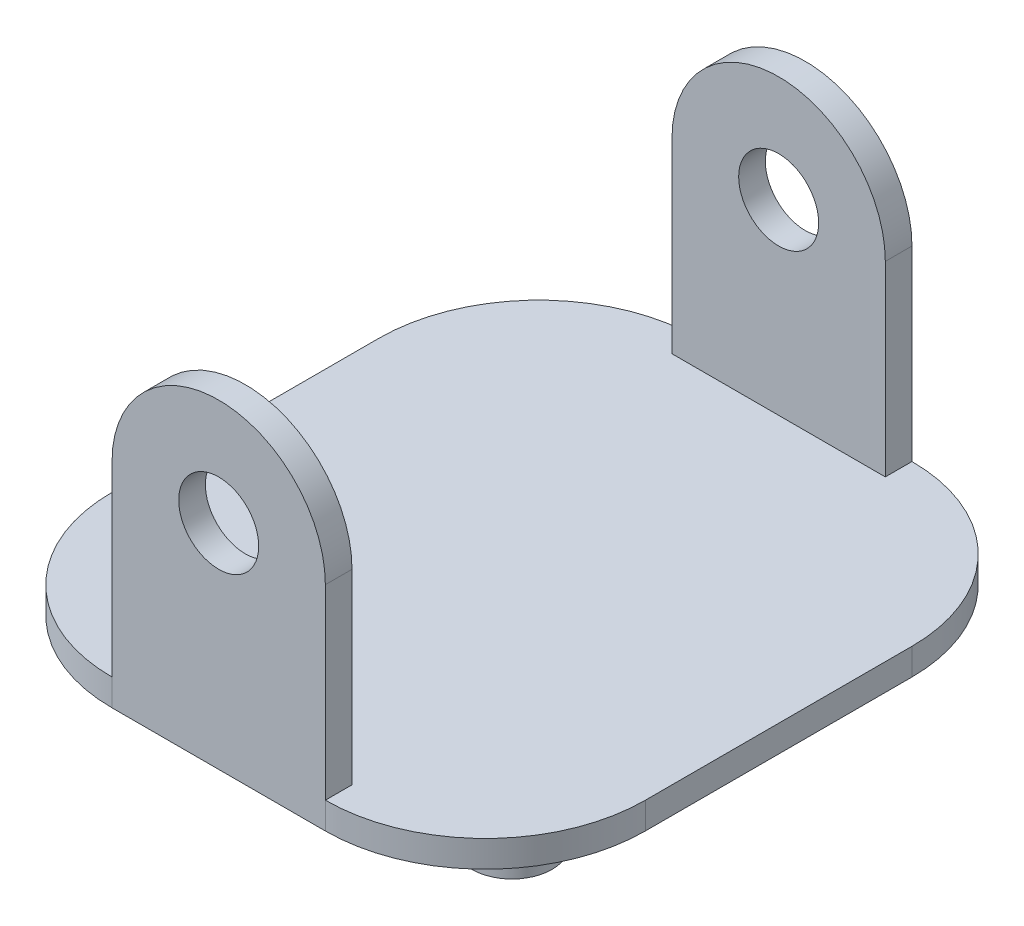
SolidWorks part; units mm, degrees
ref_plane "Alzado" through (0, 0, 0) normal (0, 0, 1) x (1, 0, 0)
ref_plane "Planta" through (0, 0, 0) normal (0, 1, 0) x (1, 0, 0)
ref_plane "Vista lateral" through (0, 0, 0) normal (1, 0, 0) x (0, 0, -1)
sketch "Croquis1" plane through (0, 0, 0) normal (0, 1, 0) x (1, 0, 0)
  line L1 (-10, -11) -> (10, -11)
  line L2 (-10, -11) -> (-10, 11)
  line L3 (-10, 11) -> (10, 11)
  line L4 (10, -11) -> (10, 11)
  line L5 (-10, -11) -> (10, 11) construction
  line L6 (-10, 11) -> (10, -11) construction
  point P0 (0, 0)
  dimension "D1" = 22
  dimension "D2" = 20
extrude "Saliente-Extruir1" add sketch "Croquis1" along normal blind 1
sketch "Croquis2" plane through (0, 1, 0) normal (0, 1, 0) x (1, 0, 0)
  line L0 (0, -11) -> (0, 0) construction
  line L1 (-10, -11) -> (10, -11) construction
  line L2 (0, 0) -> (-10, 0) construction
  line L3 (-10, 11) -> (-10, -11) construction
  line L4 (-4, -11) -> (4, -11)
  line L5 (-4, -11) -> (-4, -10)
  line L6 (-4, -10) -> (4, -10)
  line L7 (4, -10) -> (4, -11)
  line L8 (4, 10) -> (4, 11)
  line L9 (-4, 10) -> (4, 10)
  line L10 (-4, 11) -> (-4, 10)
  line L11 (-4, 11) -> (4, 11)
  dimension "D1" = 8
  dimension "D2" = 1
extrude "Saliente-Extruir2" add sketch "Croquis2" along normal blind 20
sketch "Croquis3" plane through (0, 0, 11) normal (0, 0, 1) x (1, 0, 0)
  line L0 (0, 0) -> (0, 8) construction
  line L1 (-4, 21) -> (-4, 1) construction
  line L2 (-4, 8) -> (-13.0814, 8)
  line L3 (-13.0814, 8) -> (-13.0814, 28.5615)
  line L4 (-13.0814, 28.5615) -> (15.5497, 28.5615)
  line L5 (15.5497, 28.5615) -> (15.5497, 8)
  line L6 (15.5497, 8) -> (4, 8)
  line L7 (-10, 1) -> (-4, 1) construction
  circle A0 centre (0, 8) radius 1.5
  arc A1 (4, 8) -> (-4, 8) centre (0, 8) ccw
  dimension "D2" = 3
  dimension "D1" = 7
extrude "Cortar-Extruir1" cut sketch "Croquis3" against normal through all
sketch "Croquis4" plane through (0, 0, 0) normal (0, -1, 0) x (1, 0, 0)
  line L0 (-10, 11) -> (10, -11) construction
  line L1 (-10, -11) -> (10, 11) construction
  circle A0 centre (0, 0) radius 1.5
  dimension "D1" = 3
extrude "Saliente-Extruir3" add sketch "Croquis4" along normal blind 8
fillet "Redondeo1" radius 6 4 edges at (-10, 0.5, -11) (-10, 0.5, 11) (10, 0.5, -11) (10, 0.5, 11)
